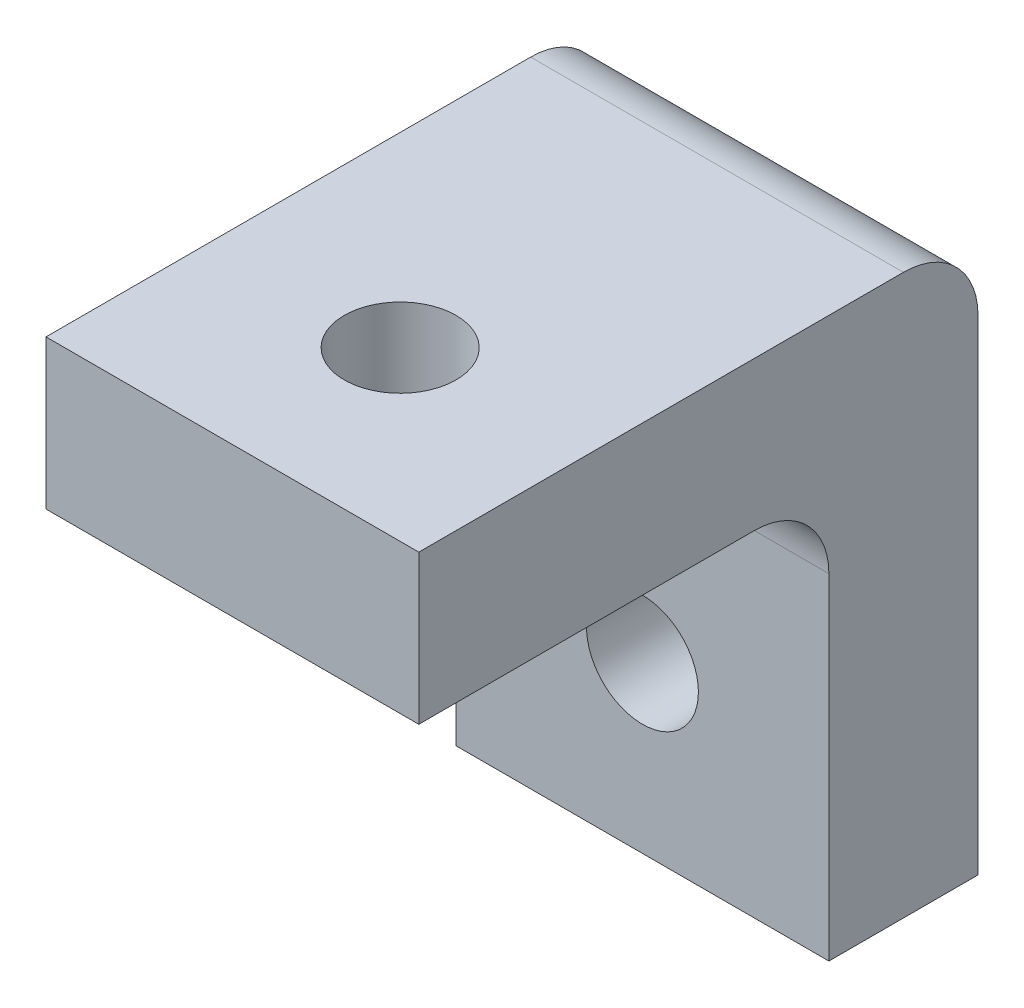
SolidWorks part; units mm, degrees
ref_plane "Front Plane" through (0, 0, 0) normal (1, 0, 0) x (0, 1, 0)
ref_plane "Top Plane" through (0, 0, 0) normal (0, 0, 1) x (0, 1, 0)
ref_plane "Right Plane" through (0, 0, 0) normal (0, 1, 0) x (-1, 0, 0)
sketch "Sketch1" plane through (0, 0, 0) normal (1, 0, 0) x (0, 1, 0)
  line L0 (0, 0) -> (0, 15)
  line L1 (0, 0) -> (-15, 0)
  line L2 (-15, 0) -> (-15, 4)
  line L3 (-15, 4) -> (-6, 4)
  line L4 (-4, 6) -> (-4, 15)
  line L5 (-4, 15) -> (0, 15)
  arc A0 (-6, 4) -> (-4, 6) centre (-6, 6) ccw
  dimension "D2" = 2
  dimension "D1" = 15
  dimension "D3" = 4
extrude "Boss-Extrude1" add sketch "Sketch1" along normal blind 10
sketch "Sketch2" plane through (0, -4, 0) normal (0, -1, 0) x (1, 0, 0)
  line L4 (0, 15) -> (0, 6)
  line L5 (0, 6) -> (10, 6)
  line L6 (10, 6) -> (10, 15)
  line L7 (10, 15) -> (0, 15)
  line L8 (0, 15) -> (0, 6)
  line L9 (0, 6) -> (10, 6)
  line L10 (10, 6) -> (10, 15)
  line L11 (10, 15) -> (0, 15)
  circle A0 centre (5, 10.5) radius 1.5
  point P2 (0, 0)
  point P5 (0, 0)
  point P7 (5, 15)
  point P9 (10, 10.5)
  dimension "D1" = 3
  dimension "D2" = 0
extrude "Cut-Extrude2" cut sketch "Sketch2" against normal through all contours A0
sketch "Sketch3" plane through (0, 0, 4) normal (0, 0, 1) x (1, 0, 0)
  line L0 (0, -15) -> (10, -15) construction
  line L1 (10, -6) -> (10, -15) construction
  line L2 (10, -6) -> (10, -15) construction
  line L3 (0, -6) -> (0, -15) construction
  line L4 (10, -15) -> (0, -15) construction
  circle A0 centre (5, -10.5) radius 1.5
  point P3 (4.2008, -10.2913)
  point P4 (0, 0)
  point P9 (5, -11.2772)
  point P10 (10, -10.5)
  point P11 (5, -15)
  point P12 (0, 0)
  point P17 (0, 0)
  point P18 (0, 0)
  dimension "D1" = 3
extrude "Cut-Extrude3" cut sketch "Sketch3" against normal through all
fillet "Fillet1" radius 2 1 edges at (5, 0, 0)
